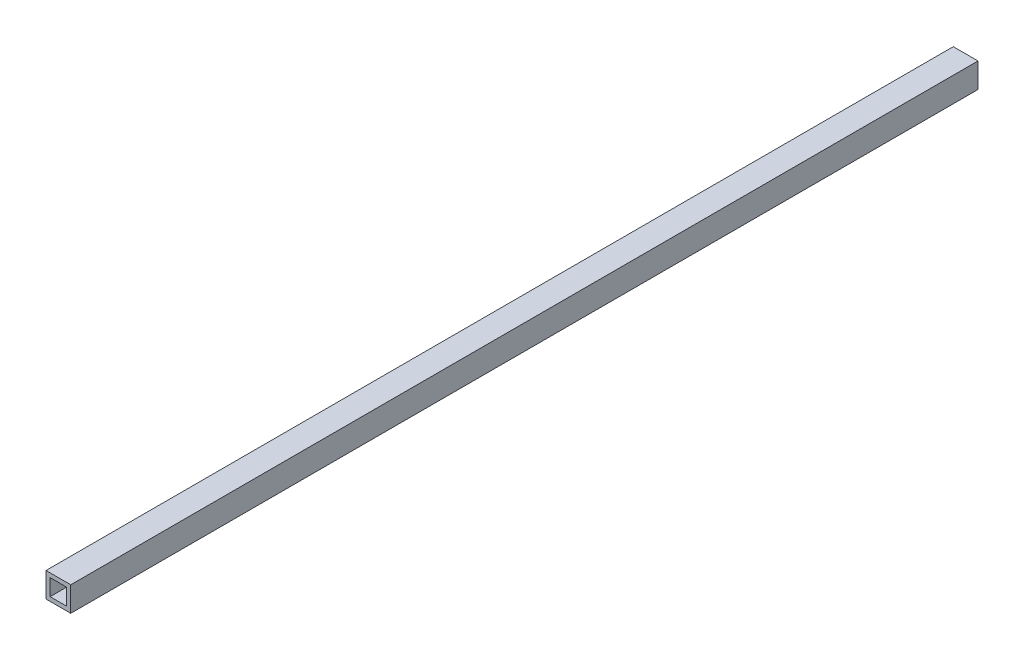
SolidWorks part; units mm, degrees
ref_plane "Front Plane" through (0, 0, 0) normal (0, 0, 1) x (1, 0, 0)
ref_plane "Top Plane" through (0, 0, 0) normal (0, 1, 0) x (1, 0, 0)
ref_plane "Right Plane" through (0, 0, 0) normal (1, 0, 0) x (0, 0, -1)
sketch "Sketch1" plane through (0, 0, 0) normal (0, 0, 1) x (1, 0, 0)
  line L1 (9.525, -9.525) -> (-9.525, -9.525)
  line L2 (9.525, -9.525) -> (9.525, 9.525)
  line L3 (9.525, 9.525) -> (-9.525, 9.525)
  line L4 (-9.525, -9.525) -> (-9.525, 9.525)
  line L5 (9.525, -9.525) -> (-9.525, 9.525) construction
  line L6 (9.525, 9.525) -> (-9.525, -9.525) construction
  line L7 (6.35, -6.35) -> (-6.35, -6.35)
  line L8 (6.35, -6.35) -> (6.35, 6.35)
  line L9 (6.35, 6.35) -> (-6.35, 6.35)
  line L10 (-6.35, -6.35) -> (-6.35, 6.35)
  line L11 (6.35, -6.35) -> (-6.35, 6.35) construction
  line L12 (6.35, 6.35) -> (-6.35, -6.35) construction
  point P0 (0, 0)
  point P6 (0, 0)
  dimension "D1" = 19.05
  dimension "D2" = 3.175
  dimension "D3" = 19.05
extrude "Boss-Extrude1" add sketch "Sketch1" along normal blind 698.5
